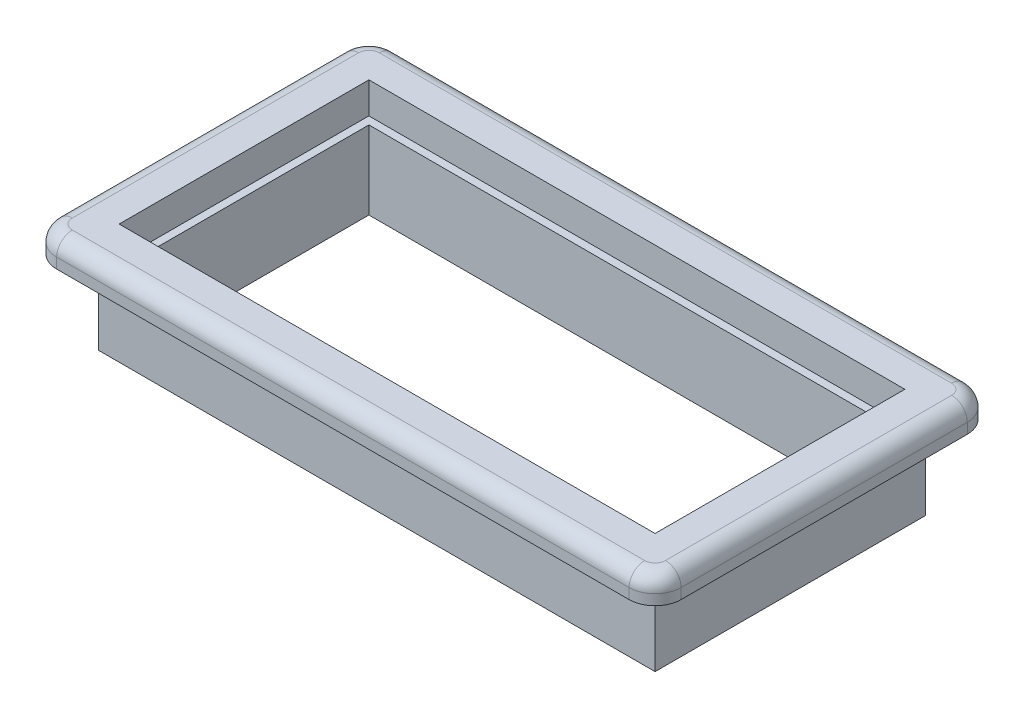
SolidWorks part; units mm, degrees
ref_plane "Front Plane" through (0, 0, 0) normal (0, 0, 1) x (1, 0, 0)
ref_plane "Top Plane" through (0, 0, 0) normal (0, 1, 0) x (1, 0, 0)
ref_plane "Right Plane" through (0, 0, 0) normal (1, 0, 0) x (0, 0, -1)
sketch "Sketch1" plane through (0, 0, 0) normal (0, 1, 0) x (1, 0, 0)
  line L1 (-55, -32.5) -> (55, -32.5)
  line L2 (-60, -27.5) -> (-60, 27.5)
  line L3 (-55, 32.5) -> (55, 32.5)
  line L4 (60, -27.5) -> (60, 27.5)
  line L5 (-60, -32.5) -> (60, 32.5) construction
  line L6 (-60, 32.5) -> (60, -32.5) construction
  line L7 (-50, -22.5) -> (50, -22.5)
  line L8 (-50, -22.5) -> (-50, 22.5)
  line L9 (-50, 22.5) -> (50, 22.5)
  line L10 (50, -22.5) -> (50, 22.5)
  line L11 (-50, -22.5) -> (50, 22.5) construction
  line L12 (-50, 22.5) -> (50, -22.5) construction
  arc A0 (-55, -32.5) -> (-60, -27.5) centre (-55, -27.5) cw
  arc A1 (55, -32.5) -> (60, -27.5) centre (55, -27.5) ccw
  arc A2 (55, 32.5) -> (60, 27.5) centre (55, 27.5) cw
  arc A3 (-60, 27.5) -> (-55, 32.5) centre (-55, 27.5) cw
  point P0 (0, 0)
  point P6 (0, 0)
  dimension "D5" = 5
  dimension "D6" = 5
  dimension "D7" = 5
  dimension "D8" = 5
  dimension "D1" = 120
  dimension "D2" = 65
  dimension "D3" = 10
  dimension "D4" = 10
extrude "Boss-Extrude1" add sketch "Sketch1" along normal blind 5
sketch "Sketch2" plane through (0, 0, 0) normal (0, -1, 0) x (1, 0, 0)
  line L0 (50, -22.5) -> (-50, -22.5) construction
  line L1 (-50, -22.5) -> (-50, 22.5) construction
  line L2 (-50, 22.5) -> (50, 22.5) construction
  line L3 (50, 22.5) -> (50, -22.5) construction
  line L4 (50, -22.5) -> (-50, -22.5)
  line L5 (-50, -22.5) -> (-50, 22.5)
  line L6 (-50, 22.5) -> (50, 22.5)
  line L7 (50, 22.5) -> (50, -22.5)
  line L8 (-53.5, 26) -> (53.5, 26)
  line L9 (53.5, 26) -> (53.5, -26)
  line L10 (53.5, -26) -> (-53.5, -26)
  line L11 (-53.5, -26) -> (-53.5, 26)
  dimension "D1" = 3.5
extrude "Boss-Extrude2" add sketch "Sketch2" along normal blind 16
fillet "Fillet1" radius 3 8 edges at (58.5355, 5, -31.0355) (60, 5, 0) (58.5355, 5, 31.0355) (0, 5, 32.5) (-58.5355, 5, 31.0355) (-60, 5, 0) (-58.5355, 5, -31.0355) (0, 5, -32.5)
sketch "Sketch3" plane through (0, 5, 0) normal (0, 1, 0) x (1, 0, 0)
  line L1 (51.5, 24) -> (-51.5, 24)
  line L2 (51.5, 24) -> (51.5, -24)
  line L3 (51.5, -24) -> (-51.5, -24)
  line L4 (-51.5, 24) -> (-51.5, -24)
  line L5 (51.5, 24) -> (-51.5, -24) construction
  line L6 (51.5, -24) -> (-51.5, 24) construction
  line L7 (50, -22.5) -> (50, 22.5) construction
  line L8 (-50, -22.5) -> (50, -22.5) construction
  line L9 (50, 22.5) -> (-50, 22.5) construction
  line L10 (-50, 22.5) -> (-50, -22.5) construction
  line L11 (50, 22.5) -> (-50, 22.5)
  line L12 (50, -22.5) -> (50, 22.5)
  line L13 (-50, 22.5) -> (-50, -22.5)
  line L14 (-50, -22.5) -> (50, -22.5)
  point P0 (0, 0)
  dimension "D1" = 1.5
  dimension "D2" = 1.5
extrude "Cut-Extrude1" cut sketch "Sketch3" against normal blind 6
